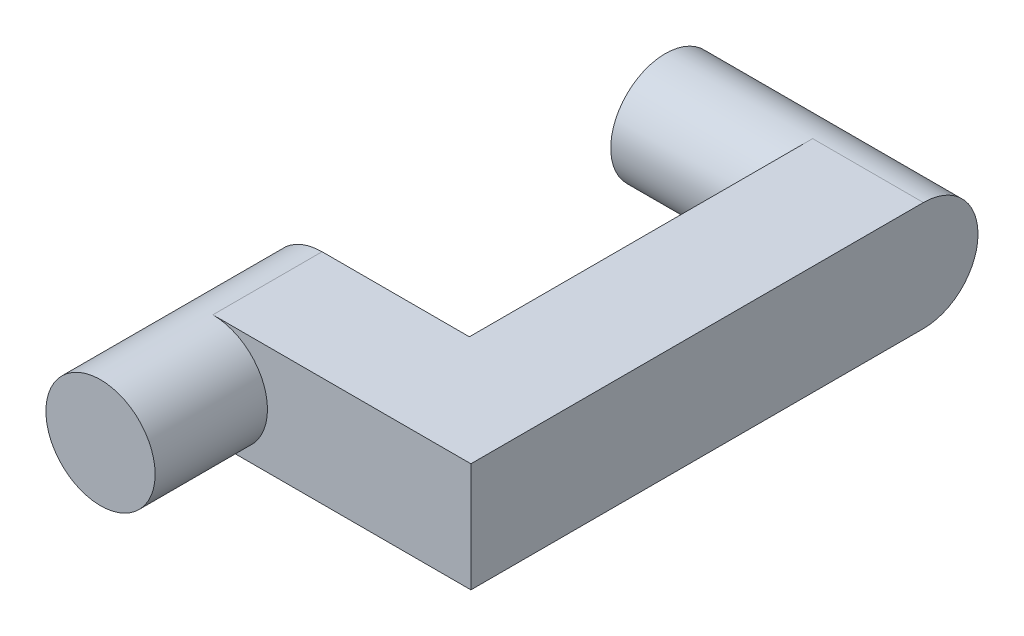
SolidWorks part; units mm, degrees
ref_plane "Front Plane" through (0, 0, 0) normal (0, 0, 1) x (1, 0, 0)
ref_plane "Top Plane" through (0, 0, 0) normal (0, 1, 0) x (1, 0, 0)
ref_plane "Right Plane" through (0, 0, 0) normal (1, 0, 0) x (0, 0, -1)
sketch "Sketch1" plane through (0, 0, 0) normal (0, 1, 0) x (1, 0, 0)
  line L1 (0, -90) -> (82.6921, -90)
  line L2 (0, -90) -> (0, -55)
  line L3 (47.2067, 55) -> (82.6921, 55)
  line L4 (82.6921, -90) -> (82.6921, 55)
  line L5 (0, -55) -> (47.2067, -55)
  line L8 (47.2067, -55) -> (47.2067, 55)
  dimension "D1" = 35
  dimension "D2" = 145
extrude "Boss-Extrude1" add sketch "Sketch1" along normal blind 35
sketch "Sketch4" plane through (47.2067, 0, 0) normal (-1, 0, 0) x (0, 0, 1)
  line L0 (-55, 35) -> (-55, 0) construction
  circle A0 centre (-55, 17.5) radius 17.5
extrude "Boss-Extrude4" add sketch "Sketch4" along normal up to surface and the other way up to surface separate body up to face at (0, 17.5, 72.5) other way up to face at (82.6921, 17.5, 17.5)
sketch "Sketch3" plane through (0, 0, 90) normal (0, 0, 1) x (1, 0, 0)
  line L0 (0, 35) -> (0, 0) construction
  circle A0 centre (0, 17.5) radius 17.5
extrude "Boss-Extrude3" add sketch "Sketch3" along normal blind 36 and the other way up to surface (35 mm away) separate body other way up to face at (23.6033, 17.5, 55)
combine bodies "Combine1" operation type add bodies to combine 103 101 104
